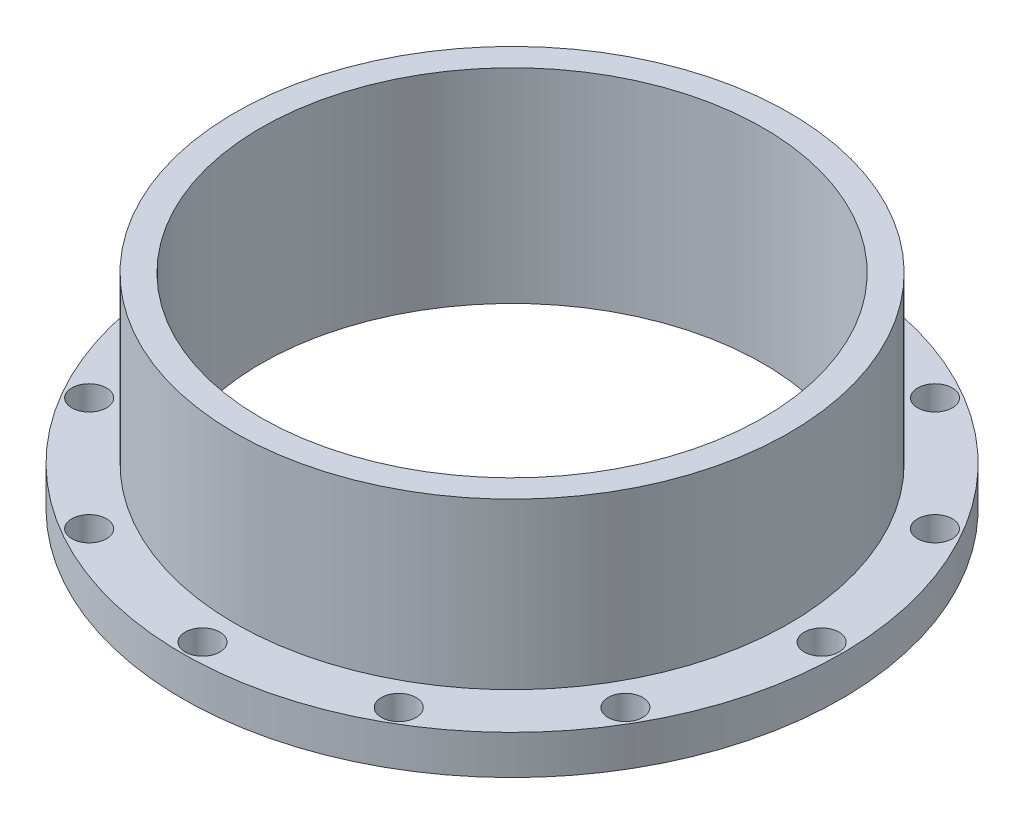
SolidWorks part; units mm, degrees
material "6061 Alloy"
ref_plane "Front Plane" through (0, 0, 0) normal (0, 0, 1) x (1, 0, 0)
ref_plane "Top Plane" through (0, 0, 0) normal (0, 1, 0) x (1, 0, 0)
ref_plane "Right Plane" through (0, 0, 0) normal (1, 0, 0) x (0, 0, -1)
sketch "Sketch4" plane through (0, 0, 0) normal (0, 1, 0) x (1, 0, 0)
  circle A0 centre (0, 0) radius 49.2125
  dimension "D1" = 98.425
extrude "Boss-Extrude2" add sketch "Sketch4" along normal blind 30.48
sketch "Sketch5" plane through (0, 30.48, 0) normal (0, 1, 0) x (1, 0, 0)
  circle A0 centre (0, 0) radius 41.402
  dimension "D1" = 82.804
extrude "Cut-Extrude3" cut sketch "Sketch5" against normal blind 24.638 flip side to cut
sketch "Sketch6" plane through (0, 30.48, 0) normal (0, 1, 0) x (1, 0, 0)
  circle A0 centre (0, 0) radius 37.5
  dimension "D1" = 75
extrude "Cut-Extrude4" cut sketch "Sketch6" against normal through all
sketch "Sketch11" plane through (0, 5.842, 0) normal (0, 1, 0) x (1, 0, 0)
  circle A0 centre (0, 0) radius 46.228 construction
  point P4 (0, 46.228)
hole_wizard "#6 (0.204) Diameter Hole2" positions "Sketch11" profile "Sketch12" hole size "#6" standard "ANSI Inch" end condition through all
sketch "Sketch12" plane through (0, 5.842, -46.228) normal (1, 0, 0) x (0, 0, 1)
  line L0 (0, 0) -> (0, 5.842)
  line L1 (0, 5.842) -> (2.5908, 5.842)
  line L2 (2.5908, 5.842) -> (2.5908, 0)
  line L5 (2.5908, 0) -> (0, 0)
  line L11 (0, -6.35) -> (0, 107.95) construction
  dimension "Thru Hole Dia." = 5.1816
  dimension "Thru Hole Depth" = 5.842
pattern_circular "CirPattern5" count 12 over 360 about axis through (0, 0, 0) along (0, 1, 0) of "#6 (0.204) Diameter Hole2"
